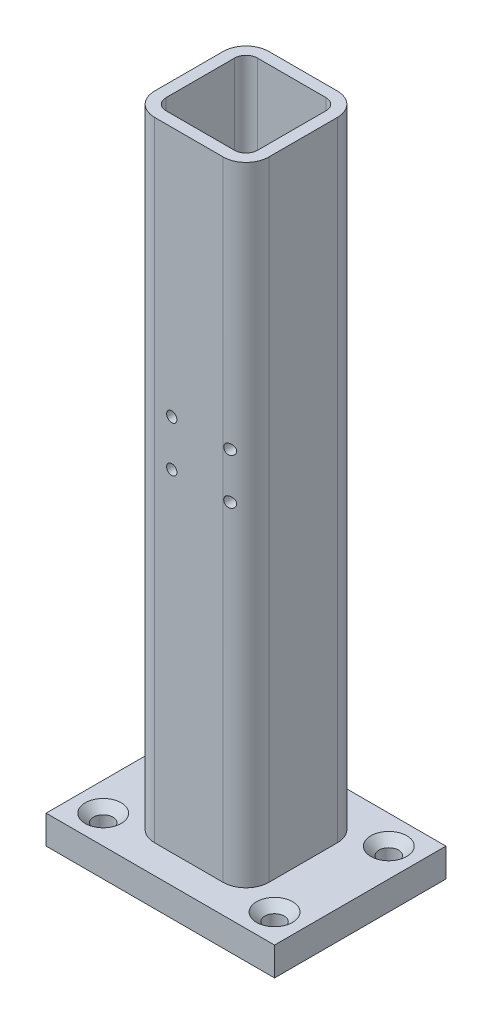
SolidWorks part; units mm, degrees
ref_plane "Front Plane" through (0, 0, 0) normal (0, 0, 1) x (1, 0, 0)
ref_plane "Top Plane" through (0, 0, 0) normal (0, 1, 0) x (1, 0, 0)
ref_plane "Right Plane" through (0, 0, 0) normal (1, 0, 0) x (0, 0, -1)
sketch3d "3DSketch1"
  line L0 (0, 0, 0) -> (0, 110, 0)
  dimension "D1" = 110
other "Square tube 20 X 20 X 2(1)"
ref_plane "Plane1" through (0, 0, 0) normal (0, 1, 0) x (1, 0, 0)
sketch "Sketch1" plane through (0, 0, 0) normal (0, 1, 0) x (1, 0, 0)
  line L0 (-6, -8) -> (6, -8)
  line L1 (-8, -6) -> (-8, 6)
  line L2 (6, 8) -> (-6, 8)
  line L3 (8, 6) -> (8, -6)
  line L4 (-6, -10) -> (6, -10)
  line L5 (-10, -6) -> (-10, 6)
  line L6 (6, 10) -> (-6, 10)
  line L7 (10, 6) -> (10, -6)
  arc A0 (10, 6) -> (6, 10) centre (6, 6) ccw
  arc A1 (6, -10) -> (10, -6) centre (6, -6) ccw
  arc A2 (-10, -6) -> (-6, -10) centre (-6, -6) ccw
  arc A3 (-6, 10) -> (-10, 6) centre (-6, 6) ccw
  arc A4 (-6, 8) -> (-8, 6) centre (-6, 6) ccw
  arc A5 (8, 6) -> (6, 8) centre (6, 6) ccw
  arc A6 (6, -8) -> (8, -6) centre (6, -6) ccw
  arc A7 (-8, -6) -> (-6, -8) centre (-6, -6) ccw
  point P0 (-10, 0)
  point P1 (10, 0)
  point P2 (0, 10)
  point P3 (0, -10)
  point P4 (0, 0)
  point P5 (-10, -10)
  point P6 (10, -10)
  point P7 (10, 10)
  point P8 (-10, 10)
  point P33 (0, 0)
  dimension "D1" = 4
  dimension "Thickness" = 2
  dimension "V_leg" = 20
sketch "Sketch2" plane through (0, 0, 0) normal (0, 1, 0) x (1, 0, 0)
  line L1 (-20, 15) -> (20, 15)
  line L2 (-20, 15) -> (-20, -15)
  line L3 (-20, -15) -> (20, -15)
  line L4 (20, 15) -> (20, -15)
  line L5 (-20, 15) -> (20, -15) construction
  line L6 (-20, -15) -> (20, 15) construction
  point P0 (0, 0)
  dimension "D1" = 30
  dimension "D2" = 40
extrude "Boss-Extrude1" add sketch "Sketch2" against normal blind 5
sketch "Sketch3" plane through (0, 0, 0) normal (0, 1, 0) x (1, 0, 0)
  line L0 (-15, 10) -> (-15, -10)
  line L1 (-15, -10) -> (15, -10)
  line L2 (15, -10) -> (15, 10)
  line L3 (15, 10) -> (-15, 10)
  line L4 (20, -15) -> (20, 15)
  line L5 (20, 15) -> (-20, 15)
  line L6 (-20, 15) -> (-20, -15)
  line L7 (-20, -15) -> (20, -15)
  line L8 (20, -15) -> (20, 15)
  line L9 (20, 15) -> (-20, 15)
  line L10 (-20, 15) -> (-20, -15)
  line L11 (-20, -15) -> (20, -15)
  point P2 (-15, 10)
  point P4 (-15, -10)
  point P6 (15, -10)
  point P7 (15, 10)
  dimension "D1" = 0
  dimension "D2" = 5
hole_wizard "CSK for M3 Countersunk Flat Head Screw1" positions "Sketch3" profile "Sketch4" countersink size "M3" standard "ISO"
sketch "Sketch4" plane through (15, 0, -10) normal (1, 0, 0) x (0, 0, 1)
  line L0 (0, 0) -> (0, 31.0215)
  line L1 (0, 31.0215) -> (1.7, 30)
  line L2 (1.7, 30) -> (1.7, 1.45)
  line L3 (1.7, 1.45) -> (3.15, 0)
  line L5 (3.15, 0) -> (0, 0)
  line L6 (-1.7, 1.45) -> (-3.15, 0) construction
  line L10 (0, 31.0215) -> (-1.7, 30) construction
  line L11 (0, -6.35) -> (0, 107.95) construction
  dimension "Hole Dia." = 3.4
  dimension "Hole Depth" = 30
  dimension "Near C'Sink Dia." = 6.3
  dimension "Near C'Sink Angle" = 90
  dimension "Drill Angle" = 118
sketch "Sketch5" plane through (0, 0, -10) normal (0, 0, -1) x (-1, 0, 0)
  circle A0 centre (3, 66.1) radius 0.9
  circle A1 centre (3, 58.1) radius 0.9
  circle A2 centre (-7, 58.1) radius 0.9
  circle A3 centre (-7, 66.1) radius 0.9
extrude "Cut-Extrude1" cut sketch "Sketch5" against normal blind 5
sketch "Sketch6" plane through (0, 0, 10) normal (0, 0, 1) x (1, 0, 0)
  circle A0 centre (-3, 66.1) radius 0.9
  circle A1 centre (7, 66.1) radius 0.9
  circle A2 centre (7, 58.1) radius 0.9
  circle A3 centre (-3, 58.1) radius 0.9
extrude "Cut-Extrude2" cut sketch "Sketch6" against normal blind 5
